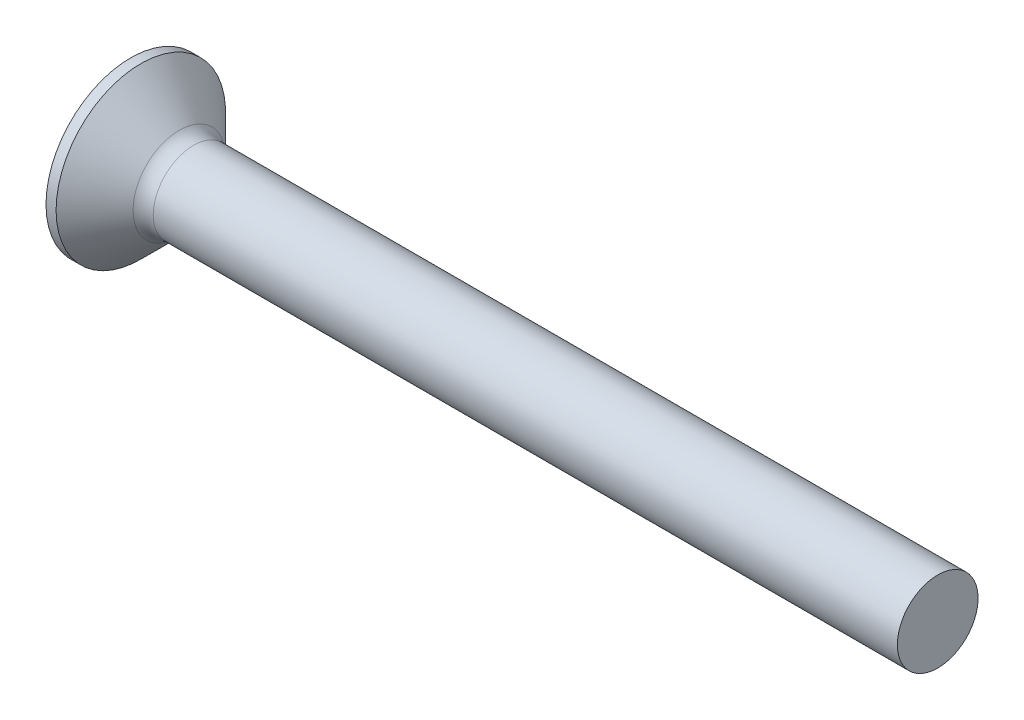
SolidWorks part; units mm, degrees
revolve "Base-Revolve" add sketch "BodySke"
sketch "BodySke" plane through (0, 0, 0) normal (0, 0, 1) x (1, 0, 0)
  line L0 (0, 0) -> (0, 4.2)
  line L1 (0, 4.2) -> (0.5, 4.2)
  line L2 (2.7, 2) -> (40, 2)
  line L3 (40, 2) -> (40, 0)
  line L4 (40, 0) -> (0, 0)
  line L5 (-6.35, 0) -> (82.55, 0) construction
  line L6 (2.7, -2) -> (40, -2) construction
  line L7 (0.5, -4.2) -> (2.7, -2) construction
  line L8 (0.5, 4.2) -> (2.7, 2)
  line L9 (0, -4.2) -> (0.5, -4.2) construction
  line L10 (3.4, 3.5875) -> (3.4, -5.9375) construction
  line L11 (0, 6.35) -> (0, -3.175) construction
  dimension "Diameter" = 4
  dimension "Length" = 40
  dimension "Head_ht" = 2.7
  dimension "Head_dia" = 8.4
  dimension "Head_ang" = 90
  dimension "D6" = 0.5
  dimension "Advance" = 0.7
  dimension "Thread_nom" = 40
cosmetic thread "ThreadCosmetic" [suppressed]
fillet "Fillet1" radius 1 1 edges at (2.7, 0, 2)
ref_plane "Plane1" through (0, 0, 0) normal (0, 0, 1) x (1, 0, 0)
ref_plane "Plane2" through (0, 0, 0) normal (0, 1, 0) x (1, 0, 0)
ref_plane "Plane3" through (0, 0, 0) normal (1, 0, 0) x (0, 0, -1)
other "Configuration Table"
sketch "Sketch3" plane through (0, 0, 0) normal (-1, 0, 0) x (0, 0, 1)
  line L0 (-0.515, 2.2) -> (0.515, 2.2)
  line L1 (0.515, 2.2) -> (0.515, -2.2)
  line L2 (0.515, -2.2) -> (-0.515, -2.2)
  line L3 (-0.515, -2.2) -> (-0.515, 2.2)
  dimension "Cross_dia" = 4.4
  dimension "Cross_width" = 1.03
  dimension "D1" = 2.2
  dimension "D2" = 0.515
ref_plane "Plane4" through (2.51, 0, 0) normal (-1, 0, 0) x (0, 0, 1)
sketch "Sketch4" plane through (2.51, 0, 0) normal (-1, 0, 0) x (0, 0, 1)
  line L0 (-0.515, 0.9486) -> (0.515, 0.9486)
  line L3 (0.515, 0.9486) -> (0.515, -0.9486)
  line L4 (0.515, -0.9486) -> (-0.515, -0.9486)
  line L5 (-0.515, -0.9486) -> (-0.515, 0.9486)
  dimension "D2" = 1.8971
  dimension "D1" = 1.03
  dimension "D4" = 0.9486
  dimension "D3" = 0.515
loft "Recess" cut profiles "Sketch3", "Sketch4"
pattern_circular "RecPat" count 2 every 90 about axis through (0, 0, 0) along (1, 0, 0) of "Recess"
sketch "RecCorSke" plane through (0, 0, 0) normal (0, 0, 1) x (1, 0, 0)
  line L0 (-3.175, 0) -> (15.875, 0) construction
  line L2 (0, 0) -> (0, 1.0265)
  line L3 (0, 1.0265) -> (2.51, 0.851)
  line L4 (2.51, 0.851) -> (2.7865, 0)
  line L5 (2.7865, 0) -> (0, 0)
  dimension "Diameter" = 1.702
  dimension "Depth" = 2.51
  dimension "Draft_angle" = 4
  dimension "Bottom_angle" = 18
revolve "RecessCore" cut sketch "RecCorSke" angle 360 about L0
sketch "ThdSchSke" plane through (0, 0, 0) normal (0, 0, 1) x (1, 0, 0)
  line L0 (3.4, -1.61) -> (3.1269, -2)
  line L1 (3.4, -1.61) -> (3.6731, -2)
  line L2 (3.6731, -2) -> (3.6731, -2.5)
  line L3 (-3.175, 0) -> (5.1513, 0) construction
  line L5 (3.6731, -2.5) -> (3.1269, -2.5)
  line L6 (3.1269, -2.5) -> (3.1269, -2)
  line L7 (0, 4.2) -> (0, -4.2) construction
  dimension "Diameter" = 4
  dimension "Thread_minor" = 3.22
  dimension "Start" = 3.4
revolve "ThreadSchematic" [suppressed] cut sketch "ThdSchSke" angle 360 about L3
pattern_linear "ThdSchPat" [suppressed]
equation "\"D1@Sketch3\" = \"Cross_dia@Sketch3\" / 2"
equation "\"D2@Sketch3\" = \"Cross_width@Sketch3\" / 2"
equation "\"Depth@RecCorSke\" = \"Cross_depth@Plane4\""
equation "\"D1@Sketch4\" = \"Cross_width@Sketch3\""
equation "\"D2@Sketch4\" = \"Cross_dia@Sketch3\" - 2.0 * \"Cross_depth@Plane4\" * tan(26.5  * 0.017453292)"
equation "\"D3@Sketch4\" = \"D1@Sketch4\" / 2"
equation "\"D4@Sketch4\" = \"D2@Sketch4\" / 2"
equation "\"Thread_length@ThreadCosmetic\" = ((sgn( (\"Length@BodySke\" - \"Advance@BodySke\" * 1.0 - \"Head_ht@BodySke\" ) - \"Thread_nom@BodySke\" )-1)*( (\"Length@BodySke\" - \"Advance@BodySke\" * 1.0 - \"Head_ht@BodySke\" ) - \"Thread_nom@BodySke\" ))/-2+ \"Thread_nom@BodySke\""
equation "\"Thread_minor@ThdSchSke\" = \"Thread_minor@ThreadCosmetic\""
equation "\"Diameter@ThdSchSke\" = \"Diameter@BodySke\""
equation "\"Overcut@ThdSchSke\" = \"Diameter@BodySke\" * 1.25"
equation "\"Start@ThdSchSke\" = 0.000001 + \"Length@BodySke\" - \"Thread_length@ThreadCosmetic\"  '---Countersunk---"
equation "\"Num_threads@ThdSchPat\" = int( \"Thread_length@ThreadCosmetic\" / \"Advance@BodySke\" + 0.999 )  + 1"
equation "\"Advance@ThdSchPat\" = \"Thread_length@ThreadCosmetic\" /  (\"Num_threads@ThdSchPat\" - 1) 'relax it"
